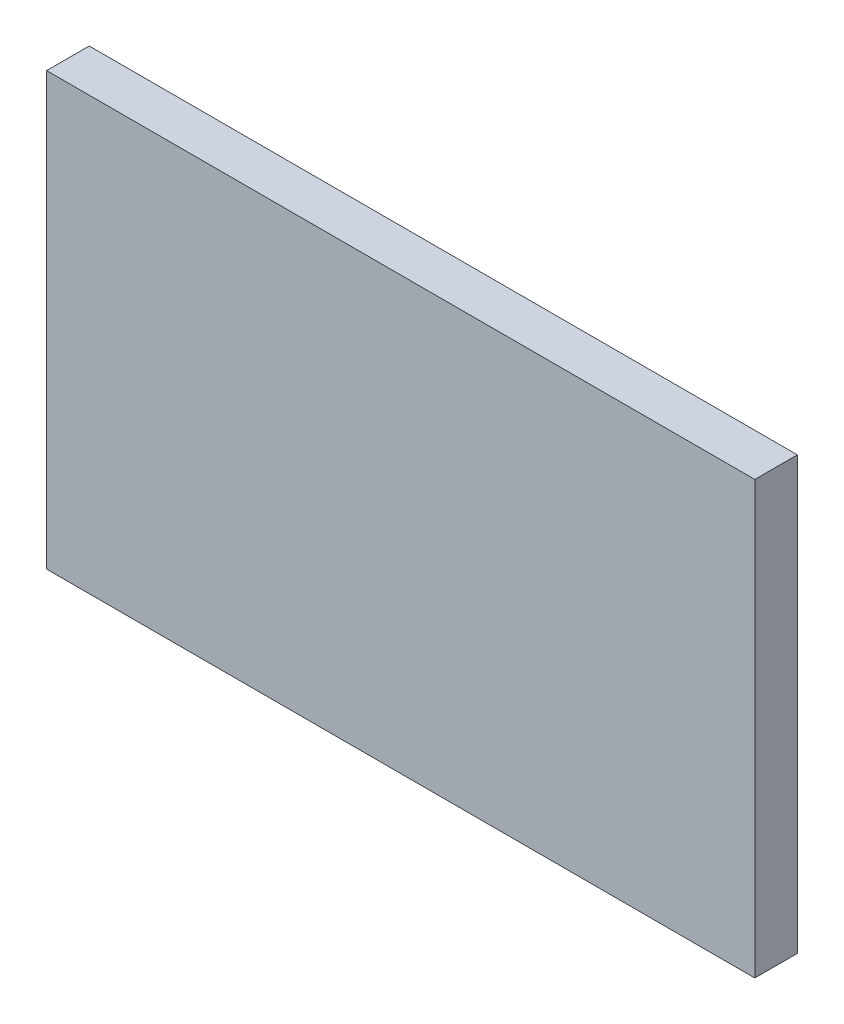
SolidWorks part; units mm, degrees
ref_plane "Plano frontal" through (0, 0, 0) normal (0, 0, 1) x (1, 0, 0)
ref_plane "Plano superior" through (0, 0, 0) normal (0, 1, 0) x (1, 0, 0)
ref_plane "Plano direito" through (0, 0, 0) normal (1, 0, 0) x (0, 0, -1)
sketch "Esboço1" plane through (0, 0, 0) normal (0, 0, 1) x (1, 0, 0)
  line L1 (0, 0) -> (166.3, 0)
  line L2 (0, 0) -> (0, 101.4)
  line L3 (0, 101.4) -> (166.3, 101.4)
  line L4 (166.3, 0) -> (166.3, 101.4)
  dimension "D1" = 166.3
  dimension "D2" = 101.4
extrude "Ressalto-extrusão1" add sketch "Esboço1" along normal blind 10
